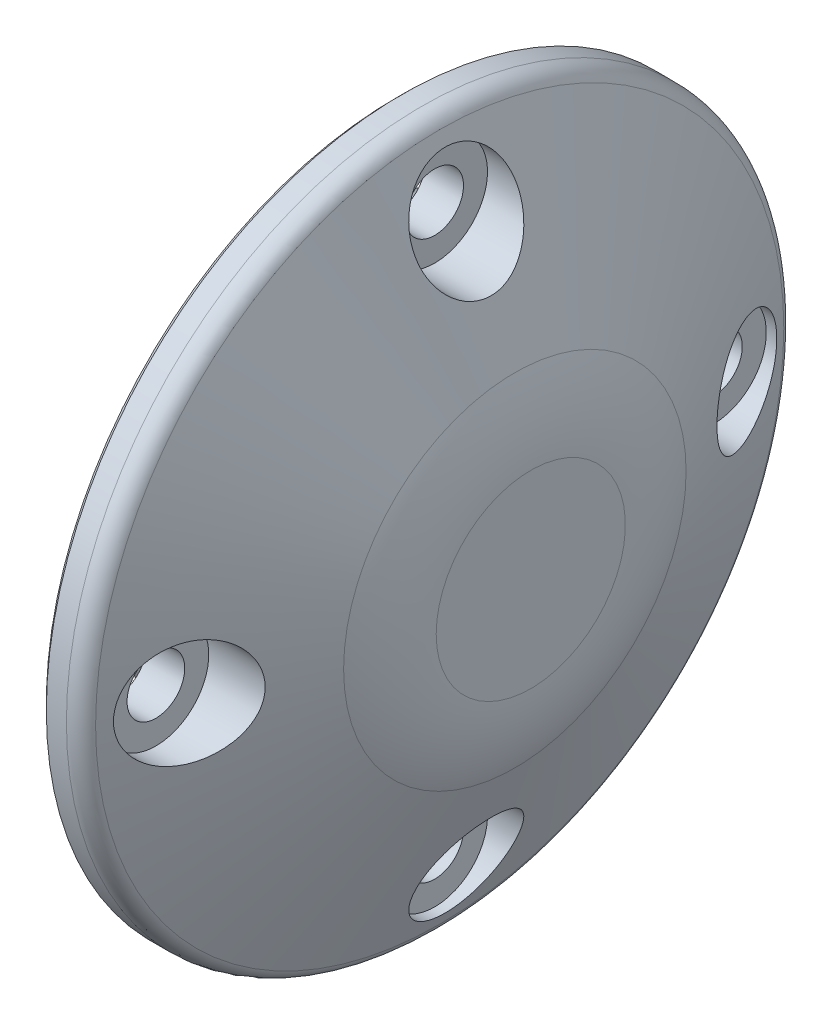
SolidWorks part; units mm, degrees
ref_plane "Front Plane" through (0, 0, 0) normal (0, 0, 1) x (1, 0, 0)
ref_plane "Top Plane" through (0, 0, 0) normal (0, 1, 0) x (1, 0, 0)
ref_plane "Right Plane" through (0, 0, 0) normal (1, 0, 0) x (0, 0, -1)
sketch "Sketch1" plane through (0, 0, 0) normal (0, 0, 1) x (1, 0, 0)
  line L0 (0, 0) -> (26.2994, 0) construction
  line L1 (-10, 7) -> (-10, 11)
  line L2 (-10, 11) -> (-6, 11)
  line L3 (-6, 11) -> (-6, 18.5)
  line L4 (-6, 18.5) -> (-4.6556, 18.5)
  line L7 (-2, 0) -> (1, 0)
  line L8 (1, 4.9201) -> (1, 0)
  line L9 (-3.7386, 17.8987) -> (0.1707, 8.9074)
  line L10 (-2, 7) -> (-2, 0)
  line L11 (-2, 7) -> (-10, 7)
  arc A1 (1, 4.9201) -> (0.1707, 8.9074) centre (-9, 4.9201) ccw
  arc A2 (-4.6556, 18.5) -> (-3.7386, 17.8987) centre (-4.6556, 17.5) cw
  point P12 (1, 7)
  point P17 (-4, 18.5)
  dimension "D6" = 7
  dimension "D8" = 10
  dimension "D9" = 1
  dimension "D1" = 4
  dimension "D2" = 11
  dimension "D3" = 18.5
  dimension "D4" = 8
  dimension "D5" = 2
  dimension "D7" = 3
  dimension "D11" = 7
  dimension "D12" = 2
revolve "Revolve1" add sketch "Sketch1" angle 360 about L0
fillet "Fillet2" radius 1 2 edges at (-2, 0, 7) (-6, 0, 11)
chamfer "Chamfer1" distance 0.3 angle 45 2 edges at (-10, 0, 11) (-6, 0, 18.5)
sketch "Sketch2" plane through (-6, 0, 0) normal (-1, 0, 0) x (0, 0, 1)
  circle A0 centre (0, 14.5) radius 1.5
  circle A1 centre (14.5, 0) radius 1.5
  circle A2 centre (0, -14.5) radius 1.5
  circle A3 centre (-14.5, 0) radius 1.5
  point P12 (0, 0)
  dimension "D2" = 3
  dimension "D114.5" = 14.5
  dimension "D3" = 4
extrude "Cut-Extrude1" cut sketch "Sketch2" against normal blind 10
ref_plane "Plane1" through (-4, 0, 0) normal (-1, 0, 0) x (0, 0, 1)
sketch "Sketch3" plane through (-4, 0, 0) normal (-1, 0, 0) x (0, 0, 1)
  circle A0 centre (0, 14.5) radius 2.75
  circle A1 centre (14.5, 0) radius 2.75
  circle A2 centre (0, -14.5) radius 2.75
  circle A3 centre (-14.5, 0) radius 2.75
  circle A4 centre (0, 14.5) radius 1.5 construction
  point P12 (0, 0)
  dimension "D2" = 5.5
  dimension "D3" = 4
extrude "Cut-Extrude2" cut sketch "Sketch3" against normal blind 10
